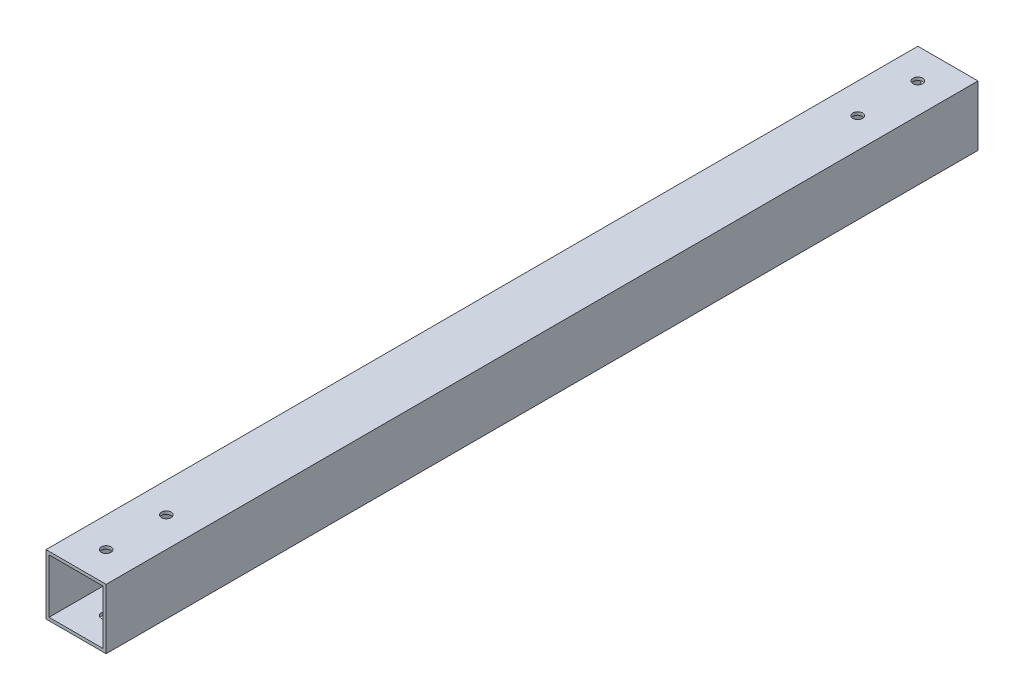
SolidWorks part; units mm, degrees
material "1060 合金"
ref_plane "前视基准面" through (0, 0, 0) normal (0, 0, 1) x (1, 0, 0)
ref_plane "上视基准面" through (0, 0, 0) normal (0, 1, 0) x (1, 0, 0)
ref_plane "右视基准面" through (0, 0, 0) normal (1, 0, 0) x (0, 0, -1)
other "Configuration Table"
sketch "草图1" plane through (0, 0, 0) normal (0, 0, 1) x (1, 0, 0)
  line L1 (0, 0) -> (20, 0)
  line L2 (0, 0) -> (0, -20)
  line L3 (0, -20) -> (20, -20)
  line L4 (20, 0) -> (20, -20)
  dimension "D1" = 20
  dimension "D2" = 20
extrude "拉伸-薄壁1" add sketch "草图1" along normal blind 290 thin
sketch "草图2" plane through (0, 0, 0) normal (0, 1, 0) x (1, 0, 0)
  line L0 (20, -290) -> (20, 0) construction
  line L1 (20, -290) -> (0, -290) construction
  circle A0 centre (10, -280) radius 1.6
  circle A1 centre (10, -260) radius 1.6
  circle A2 centre (10, -30) radius 1.6
  circle A3 centre (10, -10) radius 1.6
  dimension "D1" = 3.2
  dimension "D2" = 10
  dimension "D3" = 10
  dimension "D4" = 2
  dimension "D5" = 2
extrude "切除-拉伸1" cut sketch "草图2" against normal through all
